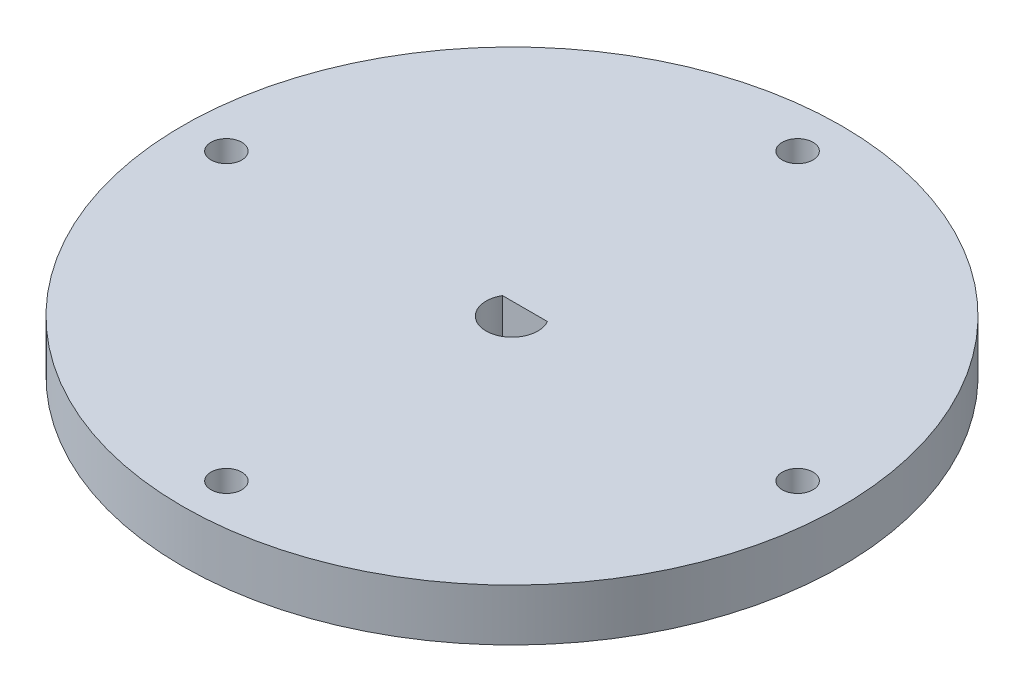
SolidWorks part; units mm, degrees
ref_plane "Front Plane" through (0, 0, 0) normal (0, 0, 1) x (1, 0, 0)
ref_plane "Top Plane" through (0, 0, 0) normal (0, 1, 0) x (1, 0, 0)
ref_plane "Right Plane" through (0, 0, 0) normal (1, 0, 0) x (0, 0, -1)
sketch "Sketch1" plane through (0, 0, 0) normal (0, 1, 0) x (1, 0, 0)
  circle A0 centre (0, 0) radius 38.1
  dimension "D1" = 76.2
extrude "Boss-Extrude1" add sketch "Sketch1" along normal blind 6
sketch "Sketch3" plane through (0, 6, 0) normal (0, 1, 0) x (1, 0, 0)
  line L0 (0, 0) -> (33.02, 0) construction
  circle A0 centre (33.02, 0) radius 1.778
  dimension "D1" = 3.556
  dimension "D2" = 33.02
extrude "Cut-Extrude1" cut sketch "Sketch3" against normal through all
pattern_circular "CirPattern1" count 4 over 360 about axis through (0, 0, 0) along (0, 1, 0) of "Cut-Extrude1"
sketch "Sketch4" plane through (0, 6, 0) normal (0, 1, 0) x (1, 0, 0)
  line L0 (-2.5981, 1.5) -> (2.5981, 1.5)
  arc A0 (-2.5981, 1.5) -> (2.5981, 1.5) centre (0, 0) ccw
  dimension "D1" = 6
  dimension "D2" = 1.5
extrude "Cut-Extrude2" cut sketch "Sketch4" against normal through all
